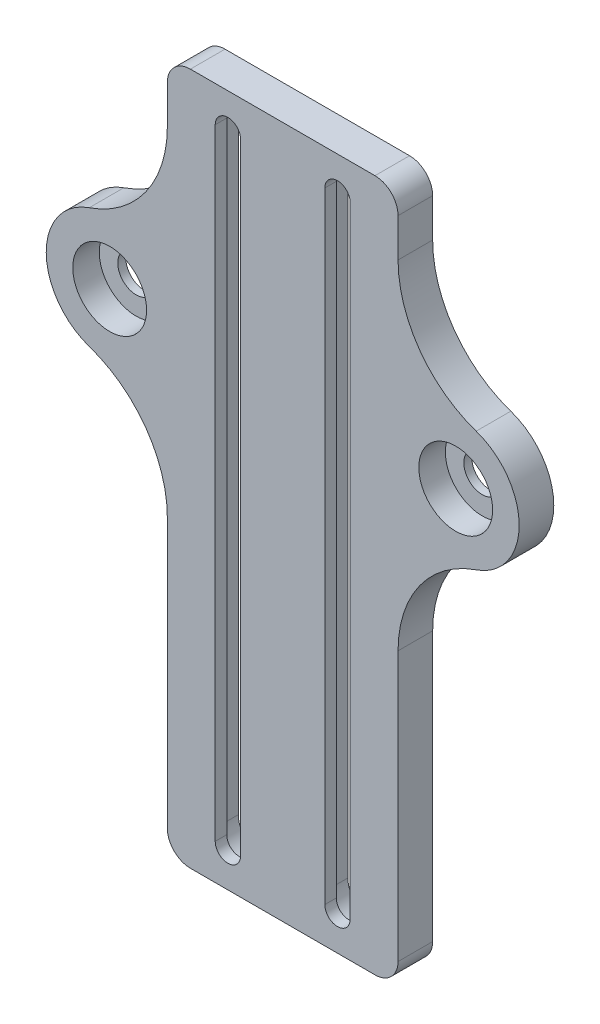
SolidWorks part; units mm, degrees
ref_plane "Front Plane" through (0, 0, 0) normal (0, 0, 1) x (1, 0, 0)
ref_plane "Top Plane" through (0, 0, 0) normal (0, 1, 0) x (1, 0, 0)
ref_plane "Right Plane" through (0, 0, 0) normal (1, 0, 0) x (0, 0, -1)
sketch "Sketch1" plane through (0, 0, 0) normal (0, 0, 1) x (1, 0, 0)
  line L0 (0, 30) -> (0, 10) construction
  line L1 (-10, -30) -> (10, -30)
  line L2 (-10, -30) -> (-10, -4.6714)
  line L3 (-10, 30) -> (10, 30)
  line L4 (10, -30) -> (10, -4.6714)
  line L5 (-10, -30) -> (10, 30) construction
  line L6 (-10, 30) -> (10, -30) construction
  line L7 (0, 10) -> (-15, 10) construction
  line L8 (-15, 10) -> (15, 10) construction
  line L9 (-10, 24.6714) -> (-10, 30)
  line L10 (10, 24.6714) -> (10, 30)
  arc A0 (-16.7742, 15.206) -> (-16.7742, 4.794) centre (-15, 10) ccw
  arc A1 (16.7742, 4.794) -> (16.7742, 15.206) centre (15, 10) ccw
  arc A2 (-16.7742, 15.206) -> (-10, 24.6714) centre (-20, 24.6714) ccw
  arc A3 (16.7742, 15.206) -> (10, 24.6714) centre (20, 24.6714) cw
  arc A4 (-10, -4.6714) -> (-16.7742, 4.794) centre (-20, -4.6714) ccw
  arc A5 (10, -4.6714) -> (16.7742, 4.794) centre (20, -4.6714) cw
  point P0 (0, 0)
  point P16 (-10, 12.2913)
  point P19 (10, 12.2913)
  dimension "D6" = 11
  dimension "D7" = 11
  dimension "D8" = 10
  dimension "D9" = 10
  dimension "D10" = 10
  dimension "D11" = 10
  dimension "D1" = 20
  dimension "D2" = 60
  dimension "D3" = 20
  dimension "D4" = 15
  dimension "D5" = 30
extrude "Boss-Extrude1" add sketch "Sketch1" along normal blind 3
sketch "Sketch2" plane through (0, 0, 3) normal (0, 0, 1) x (1, 0, 0)
  line L0 (0, 30) -> (0, 26.9) construction
  line L1 (10, 30) -> (-10, 30) construction
  line L2 (0, 26.9) -> (-4.75, 26.9) construction
  line L3 (-4.75, 26.9) -> (4.75, 26.9) construction
  line L4 (-4.75, 26.9) -> (-4.75, -26.9) construction
  line L5 (-3.65, 26.9) -> (-3.65, -26.9)
  line L6 (-5.85, 26.9) -> (-5.85, -26.9)
  line L7 (4.75, 26.9) -> (4.75, -26.9) construction
  line L8 (5.85, 26.9) -> (5.85, -26.9)
  line L9 (3.65, 26.9) -> (3.65, -26.9)
  line L10 (-10, -30) -> (10, -30) construction
  arc A0 (-3.65, 26.9) -> (-5.85, 26.9) centre (-4.75, 26.9) ccw
  arc A1 (-5.85, -26.9) -> (-3.65, -26.9) centre (-4.75, -26.9) ccw
  arc A2 (5.85, 26.9) -> (3.65, 26.9) centre (4.75, 26.9) ccw
  arc A3 (3.65, -26.9) -> (5.85, -26.9) centre (4.75, -26.9) ccw
  circle A4 centre (-15, 10) radius 1.6
  circle A5 centre (15, 10) radius 1.6
  point P5 (-4.75, 0)
  point P13 (4.75, 0)
  dimension "D4" = 1.1
  dimension "D5" = 1.1
  dimension "D7" = 3.1
  dimension "D8" = 3.2
  dimension "D9" = 3.2
  dimension "D1" = 3.1
  dimension "D2" = 4.75
  dimension "D3" = 9.5
  dimension "D6" = 3.1
extrude "Cut-Extrude1" cut sketch "Sketch2" against normal through all
sketch "Sketch3" plane through (0, 0, 3) normal (0, 0, 1) x (1, 0, 0)
  circle A0 centre (-15, 10) radius 3.2
  circle A1 centre (15, 10) radius 3.2
  dimension "D1" = 6.4
  dimension "D2" = 6.4
extrude "Cut-Extrude2" cut sketch "Sketch3" against normal blind 2.3
sketch "Sketch4" plane through (0, 0, 0) normal (0, 0, -1) x (-1, 0, 0)
  line L0 (-4.75, 26.9) -> (-4.75, -26.9) construction
  line L1 (-2.65, 26.9) -> (-2.65, -26.9)
  line L2 (-6.85, 26.9) -> (-6.85, -26.9)
  line L3 (4.75, -26.9) -> (4.75, 26.9) construction
  line L4 (2.65, -26.9) -> (2.65, 26.9)
  line L9 (6.85, -26.9) -> (6.85, 26.9)
  arc A6 (-2.65, 26.9) -> (-6.85, 26.9) centre (-4.75, 26.9) ccw
  arc A7 (-6.85, -26.9) -> (-2.65, -26.9) centre (-4.75, -26.9) ccw
  arc A8 (2.65, -26.9) -> (6.85, -26.9) centre (4.75, -26.9) ccw
  arc A9 (6.85, 26.9) -> (2.65, 26.9) centre (4.75, 26.9) ccw
  point P3 (-4.75, 0)
  point P10 (4.75, 0)
  dimension "D1" = 2.1
  dimension "D2" = 2.1
extrude "Cut-Extrude3" cut sketch "Sketch4" against normal blind 2
fillet "Fillet1" radius 2 4 edges at (-10, -30, 1.5) (10, -30, 1.5) (-10, 30, 1.5) (10, 30, 1.5)
